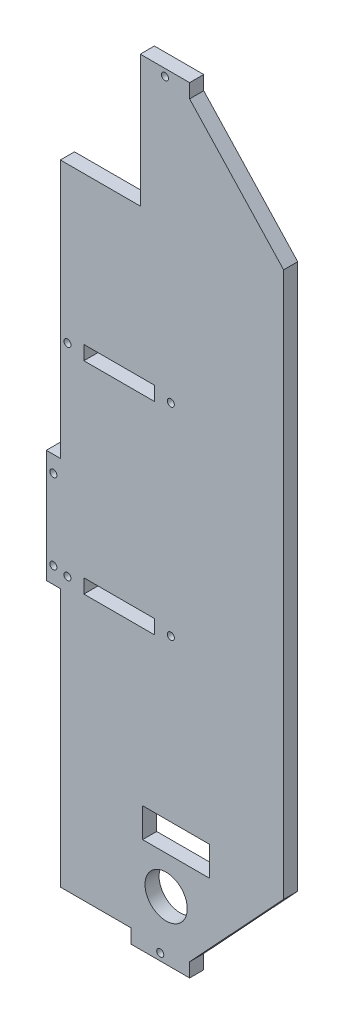
SolidWorks part; units mm, degrees
ref_plane "Plan de face" through (0, 0, 0) normal (0, 0, 1) x (1, 0, 0)
ref_plane "Plan de dessus" through (0, 0, 0) normal (0, 1, 0) x (1, 0, 0)
ref_plane "Plan de droite" through (0, 0, 0) normal (1, 0, 0) x (0, 0, -1)
sketch "Esquisse1" plane through (0, 0, 0) normal (0, 0, 1) x (1, 0, 0)
  line L1 (0, 0) -> (148, 0)
  line L2 (0, 0) -> (0, 330)
  line L3 (0, 330) -> (148, 330)
  line L4 (148, 0) -> (148, 330)
  dimension "D1" = 148
  dimension "D2" = 330
extrude "Boss.-Extru.1" add sketch "Esquisse1" along normal blind 6
sketch "Esquisse2" plane through (0, 0, 6) normal (0, 0, 1) x (1, 0, 0)
  line L0 (0, 330) -> (0, 0) construction
  line L1 (0, 0) -> (148, 0) construction
  line L2 (30, 0) -> (60, 0)
  line L3 (30, 0) -> (30, 6)
  line L4 (30, 6) -> (60, 6)
  line L5 (60, 0) -> (60, 6)
  line L6 (0, 330) -> (0, 0) construction
  line L7 (148, 330) -> (0, 330) construction
  line L8 (110, 0) -> (140, 0)
  line L9 (110, 0) -> (110, 6)
  line L10 (110, 6) -> (140, 6)
  line L11 (140, 0) -> (140, 6)
  line L12 (30, 330) -> (60, 330)
  line L13 (30, 330) -> (30, 324)
  line L14 (30, 324) -> (60, 324)
  line L15 (60, 330) -> (60, 324)
  line L17 (102, 330) -> (132, 330)
  line L18 (102, 330) -> (102, 324)
  line L19 (102, 324) -> (132, 324)
  line L20 (132, 330) -> (132, 324)
  line L21 (0, 265) -> (6, 265)
  line L22 (0, 265) -> (0, 225)
  line L23 (0, 225) -> (6, 225)
  line L24 (6, 265) -> (6, 225)
  line L25 (0, 185) -> (6, 185)
  line L26 (0, 185) -> (0, 145)
  line L27 (0, 145) -> (6, 145)
  line L28 (6, 185) -> (6, 145)
  line L29 (0, 105) -> (6, 105)
  line L30 (0, 105) -> (0, 65)
  line L31 (0, 65) -> (6, 65)
  line L32 (6, 105) -> (6, 65)
  line L33 (148, 0) -> (148, 330) construction
  dimension "D1" = 6
  dimension "D2" = 30
  dimension "D3" = 30
  dimension "D4" = 8
  dimension "D5" = 30
  dimension "D6" = 6
  dimension "D7" = 6
  dimension "D8" = 65
  dimension "D9" = 40
  dimension "D10" = 40
  dimension "D11" = 40
  dimension "D12" = 40
  dimension "D13" = 40
  dimension "D14" = 42
  dimension "D15" = 30
  dimension "D16" = 6
  dimension "D17" = 30
  dimension "D18" = 30
  dimension "D19" = 6
extrude "Enlèv. mat.-Extru.1" cut sketch "Esquisse2" against normal blind 6
sketch "Esquisse5" plane through (0, 0, 6) normal (0, 0, 1) x (1, 0, 0)
  line L0 (0, 65) -> (0, 0) construction
  line L1 (41.5, 280) -> (71.5, 280)
  line L2 (41.5, 280) -> (41.5, 274)
  line L11 (41.5, 274) -> (71.5, 274)
  line L12 (71.5, 280) -> (71.5, 274)
  line L13 (0, 145) -> (0, 105) construction
  line L16 (30, 330) -> (0, 330) construction
  line L19 (41.5, 135) -> (71.5, 135)
  line L20 (41.5, 135) -> (41.5, 132)
  line L21 (41.5, 132) -> (71.5, 132)
  line L22 (71.5, 135) -> (71.5, 132)
  dimension "D13" = 30
  dimension "D14" = 41.5
  dimension "D15" = 50
  dimension "D16" = 6
  dimension "D17" = 3
  dimension "D18" = 30
  dimension "D19" = 41.5
  dimension "D20" = 139
sketch "Esquisse6" plane through (0, 0, 6) normal (0, 0, 1) x (1, 0, 0)
  line L1 (0, 145) -> (0, 105) construction
  line L2 (110, 116) -> (104, 116)
  line L3 (110, 116) -> (110, 56)
  line L4 (110, 56) -> (104, 56)
  line L13 (104, 116) -> (104, 56)
  line L14 (60, 0) -> (110, 0) construction
  line L15 (110, 224) -> (104, 224)
  line L16 (110, 224) -> (110, 164)
  line L17 (110, 164) -> (104, 164)
  line L18 (104, 224) -> (104, 164)
  dimension "D2" = 6
  dimension "D5" = 6
  dimension "D12" = 56
  dimension "D13" = 48
  dimension "D14" = 60
  dimension "D15" = 60
  dimension "D16" = 104
  dimension "D17" = 104
extrude "Enlèv. mat.-Extru.4" cut sketch "Esquisse6" against normal blind 10
sketch "Esquisse8" plane through (148, 0, 0) normal (1, 0, 0) x (0, 0, -1)
  line L1 (-6, 330) -> (0, 330)
  line L2 (-6, 330) -> (-6, 0)
  line L3 (-6, 0) -> (0, 0)
  line L4 (0, 330) -> (0, 0)
extrude "Boss.-Extru.2" add sketch "Esquisse8" along normal blind 57
sketch "Esquisse9" plane through (0, 0, 6) normal (0, 0, 1) x (1, 0, 0)
  line L0 (165, 0) -> (205, 0)
  line L1 (140, 0) -> (205, 0) construction
  line L2 (205, 0) -> (205, 49)
  line L3 (205, 330) -> (205, 0) construction
  line L4 (165, 0) -> (165, 6)
  line L5 (165, 330) -> (205, 330)
  line L6 (205, 330) -> (132, 330) construction
  line L7 (205, 330) -> (205, 281)
  line L8 (165, 330) -> (165, 324)
  line L9 (165, 6) -> (205, 49)
  line L10 (165, 324) -> (205, 281)
  dimension "D1" = 40
  dimension "D2" = 49
  dimension "D3" = 40
  dimension "D4" = 49
  dimension "D5" = 6
  dimension "D6" = 6
extrude "Enlèv. mat.-Extru.5" cut sketch "Esquisse9" against normal through all
sketch "Esquisse10" plane through (0, 0, 6) normal (0, 0, 1) x (1, 0, 0)
  line L9 (205, 49) -> (205, 281) construction
  line L10 (120, 211) -> (150, 211)
  line L13 (120, 211) -> (120, 205)
  line L14 (120, 205) -> (150, 205)
  line L15 (150, 211) -> (150, 205)
  line L16 (165, 330) -> (132, 330) construction
  line L18 (120, 125) -> (150, 125)
  line L19 (120, 125) -> (120, 119)
  line L20 (120, 119) -> (150, 119)
  line L21 (150, 125) -> (150, 119)
  dimension "D9" = 30
  dimension "D10" = 55
  dimension "D11" = 6
  dimension "D12" = 119
  dimension "D13" = 6
  dimension "D14" = 30
  dimension "D15" = 55
  dimension "D16" = 80
extrude "Enlèv. mat.-Extru.6" cut sketch "Esquisse10" against normal through all
sketch "Esquisse13" plane through (0, 0, 0) normal (0, 0, -1) x (-1, 0, 0)
  line L0 (-102, 330) -> (-60, 330) construction
  line L1 (-88, 330) -> (-144, 330)
  line L2 (-88, 330) -> (-88, 280)
  line L3 (-110, 274) -> (-144, 274)
  line L4 (-144, 330) -> (-144, 274)
  line L5 (-60, 324) -> (-60, 330) construction
  line L7 (-30, 324) -> (-60, 324) construction
  line L9 (-88, 280) -> (-110, 280)
  line L10 (-110, 274) -> (-110, 280)
  point P6 (-60, 327)
  dimension "D1" = 22
  dimension "D2" = 56
  dimension "D3" = 28
  dimension "D4" = 44
  dimension "D5" = 34
extrude "Enlèv. mat.-Extru.9" cut sketch "Esquisse13" against normal through all
sketch "Esquisse15" plane through (0, 0, 0) normal (0, 0, -1) x (-1, 0, 0)
  line L0 (-110, 0) -> (-110, 116)
  line L1 (-110, 280) -> (-88, 280)
  line L2 (-110, 164) -> (-110, 280)
  line L3 (0, 0) -> (0, 330)
  line L4 (0, 0) -> (-110, 0)
  line L5 (-88, 280) -> (-88, 330)
  line L6 (-88, 330) -> (0, 330)
  line L7 (-110, 116) -> (-104, 116)
  line L9 (-110, 164) -> (-104, 164)
  line L10 (-104, 116) -> (-104, 164)
extrude "Enlèv. mat.-Extru.11" cut sketch "Esquisse15" against normal blind 10
sketch "Esquisse16" plane through (0, 0, 0) normal (0, 0, -1) x (-1, 0, 0)
  line L0 (-140, 0) -> (-165, 0) construction
  line L1 (-165, 6) -> (-165, 0) construction
  line L2 (-104, 116) -> (-110, 116) construction
  line L3 (-104, 164) -> (-104, 116) construction
  line L4 (-110, 164) -> (-104, 164) construction
  line L5 (-165, 330) -> (-144, 330) construction
  line L6 (-165, 330) -> (-165, 324) construction
  line L7 (-150, 119) -> (-150, 125) construction
  line L8 (-120, 119) -> (-150, 119) construction
  line L9 (-120, 125) -> (-120, 119) construction
  line L10 (-120, 205) -> (-150, 205) construction
  line L11 (-120, 211) -> (-120, 205) construction
  line L12 (-150, 205) -> (-150, 211) construction
  circle A0 centre (-152.5, 3) radius 1.5
  circle A1 centre (-107, 123) radius 1.5
  circle A2 centre (-107, 157) radius 1.5
  circle A3 centre (-154.5, 327) radius 1.5
  circle A4 centre (-157, 122) radius 1.5
  circle A5 centre (-157, 208) radius 1.5
  circle A6 centre (-113, 122) radius 1.5
  circle A7 centre (-113, 208) radius 1.5
  point P12 (-107, 116)
  dimension "D1" = 3
  dimension "D2" = 3
  dimension "D3" = 12.5
  dimension "D4" = 3
  dimension "D5" = 7
  dimension "D6" = 3
  dimension "D7" = 3
  dimension "D8" = 3
  dimension "D9" = 7
  dimension "D10" = 3
  dimension "D11" = 3
  dimension "D12" = 10.5
  dimension "D13" = 3
  dimension "D14" = 7
  dimension "D15" = 3
  dimension "D16" = 3
  dimension "D17" = 3
  dimension "D18" = 7
  dimension "D19" = 3
  dimension "D20" = 3
  dimension "D21" = 7
  dimension "D22" = 3
  dimension "D23" = 3
  dimension "D24" = 7
extrude "Enlèv. mat.-Extru.12" cut sketch "Esquisse16" against normal blind 6
sketch "Esquisse17" plane through (0, 0, 0) normal (0, 0, -1) x (-1, 0, 0)
  circle A0 centre (-152.5, 3) radius 2.995
  circle A1 centre (-107, 123) radius 2.995
  circle A2 centre (-107, 157) radius 2.995
  circle A3 centre (-154.5, 327) radius 2.995
  dimension "D1" = 5.99
  dimension "D2" = 5.99
  dimension "D3" = 5.99
  dimension "D4" = 5.99
extrude "Enlèv. mat.-Extru.13" cut sketch "Esquisse17" against normal blind 3
sketch "Esquisse18" plane through (0, 0, 0) normal (0, 0, -1) x (-1, 0, 0)
  line L1 (-145, 41) -> (-173.5, 41)
  line L2 (-145, 41) -> (-145, 53.5)
  line L3 (-145, 53.5) -> (-173.5, 53.5)
  line L4 (-173.5, 41) -> (-173.5, 53.5)
  line L5 (-140, 0) -> (-165, 0) construction
  circle A0 centre (-155, 25) radius 9
  dimension "D4" = 18
  dimension "D6" = 25
  dimension "D1" = 28.5
  dimension "D2" = 12.5
  dimension "D5" = 16
extrude "Enlèv. mat.-Extru.14" cut sketch "Esquisse18" against normal through all
extrude "Enlèv. mat.-Extru.15" cut sketch "Esquisse5" against normal through all
